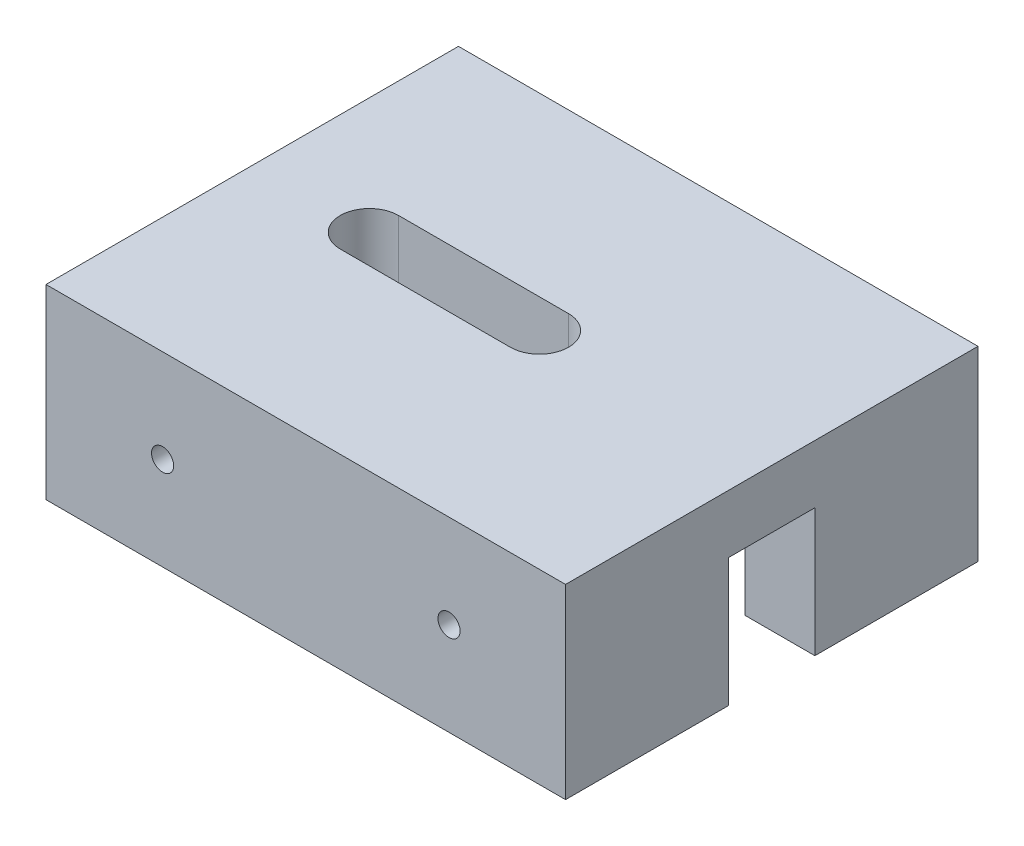
SolidWorks part; units mm, degrees
ref_plane "Front Plane" through (0, 0, 0) normal (0, 0, 1) x (1, 0, 0)
ref_plane "Top Plane" through (0, 0, 0) normal (0, 1, 0) x (1, 0, 0)
ref_plane "Right Plane" through (0, 0, 0) normal (1, 0, 0) x (0, 0, -1)
sketch "Sketch2" plane through (0, 0, 0) normal (0, 0, 1) x (1, 0, 0)
  line L0 (0, 0) -> (0, 8)
  line L1 (0, 8) -> (22.2964, 8)
  line L2 (22.2964, 8) -> (22.2964, 0)
  line L10 (0, 0) -> (22.2964, 0)
  dimension "D1" = 8
  dimension "D2" = 22.2964
extrude "Boss-Extrude1" add sketch "Sketch2" along normal blind 17.7
sketch "Sketch3" plane through (0, 0, 0) normal (0, -1, 0) x (1, 0, 0)
  line L0 (0, 15.2) -> (19.2964, 15.2)
  line L1 (0, 17.7) -> (0, 0) construction
  line L2 (19.2964, 15.2) -> (19.2964, 10.7)
  line L3 (19.2964, 10.7) -> (22.2964, 10.7)
  line L4 (22.2964, 17.7) -> (22.2964, 0) construction
  line L5 (22.2964, 10.7) -> (22.2964, 7)
  line L6 (22.2964, 7) -> (19.2964, 7)
  line L7 (19.2964, 7) -> (19.2964, 2.5)
  line L8 (19.2964, 2.5) -> (0, 2.5)
  line L9 (0, 2.5) -> (0, 15.2)
  dimension "D1" = 2.5
  dimension "D2" = 2.5
  dimension "D3" = 7
  dimension "D4" = 7
  dimension "D5" = 3
extrude "Cut-Extrude2" cut sketch "Sketch3" against normal blind 5.5
sketch "Sketch4" plane through (0, 5.5, 0) normal (0, -1, 0) x (1, 0, 0)
  line L0 (5, 8.8208) -> (12.2964, 8.8208) construction
  line L1 (5, 10.0708) -> (12.2964, 10.0708)
  line L2 (5, 7.5708) -> (12.2964, 7.5708)
  line L3 (0, 15.2) -> (0, 2.5) construction
  line L4 (22.2964, 7) -> (22.2964, 10.7) construction
  arc A0 (5, 10.0708) -> (5, 7.5708) centre (5, 8.8208) ccw
  arc A1 (12.2964, 7.5708) -> (12.2964, 10.0708) centre (12.2964, 8.8208) ccw
  point P2 (8.6482, 8.8208)
  dimension "D1" = 2.5
  dimension "D2" = 5
  dimension "D3" = 10
extrude "Cut-Extrude3" cut sketch "Sketch4" against normal up to next
sketch "Sketch9" plane through (19.2964, 0, 0) normal (-1, 0, 0) x (0, 0, 1)
  line L2 (7, 5.5) -> (7, 0) construction
  line L3 (10.7, 5.5) -> (10.7, 0) construction
  line L4 (10.7, 0) -> (15.2, 0) construction
  line L5 (2.5, 0) -> (7, 0) construction
  circle A0 centre (4.75, 2.75) radius 1.5
  circle A1 centre (12.95, 2.75) radius 1.5
  dimension "D1" = 3
  dimension "D2" = 3
  dimension "D3" = 2.25
  dimension "D4" = 2.25
  dimension "D5" = 2.75
  dimension "D6" = 2.75
extrude "Cut-Extrude4" cut sketch "Sketch9" against normal blind 2
sketch "Sketch10" plane through (0, 0, 17.7) normal (0, 0, 1) x (1, 0, 0)
  line L0 (22.2964, 8) -> (0, 8) construction
  line L1 (0, 8) -> (0, 0) construction
  line L2 (22.2964, 0) -> (22.2964, 8) construction
  point P0 (17.2964, 4)
  point P1 (5.0032, 4)
  dimension "D1" = 4
  dimension "D2" = 4
  dimension "D3" = 5.0032
  dimension "D4" = 5
hole_wizard "M1.2x0.25 Tapped Hole2" positions "3DSketch3" profile "Sketch11" tap size "M1.2x0.25" standard "ANSI Metric"
sketch3d "3DSketch3"
  point P0 (17.2964, 4, 17.7)
  point P3 (5.0032, 4, 17.7)
sketch "Sketch11" plane through (17.2964, 4, 17.7) normal (1, 0, 0) x (0, -1, 0)
  line L0 (0, 0) -> (0, 2.2854)
  line L1 (0, 2.2854) -> (0.475, 2)
  line L2 (0.475, 2) -> (0.475, 0)
  line L5 (0.475, 0) -> (0, 0)
  line L10 (0, 2.2854) -> (-0.475, 2) construction
  line L11 (0, -6.35) -> (0, 107.95) construction
  dimension "Tap Drill Dia." = 0.95
  dimension "Tap Drill Depth" = 2
  dimension "Drill Angle" = 118
cosmetic thread "Hole Thread9" parameters "D1"=1.8, "D2"=1.2
cosmetic thread "Hole Thread10" parameters "D1"=1.8, "D2"=1.2
